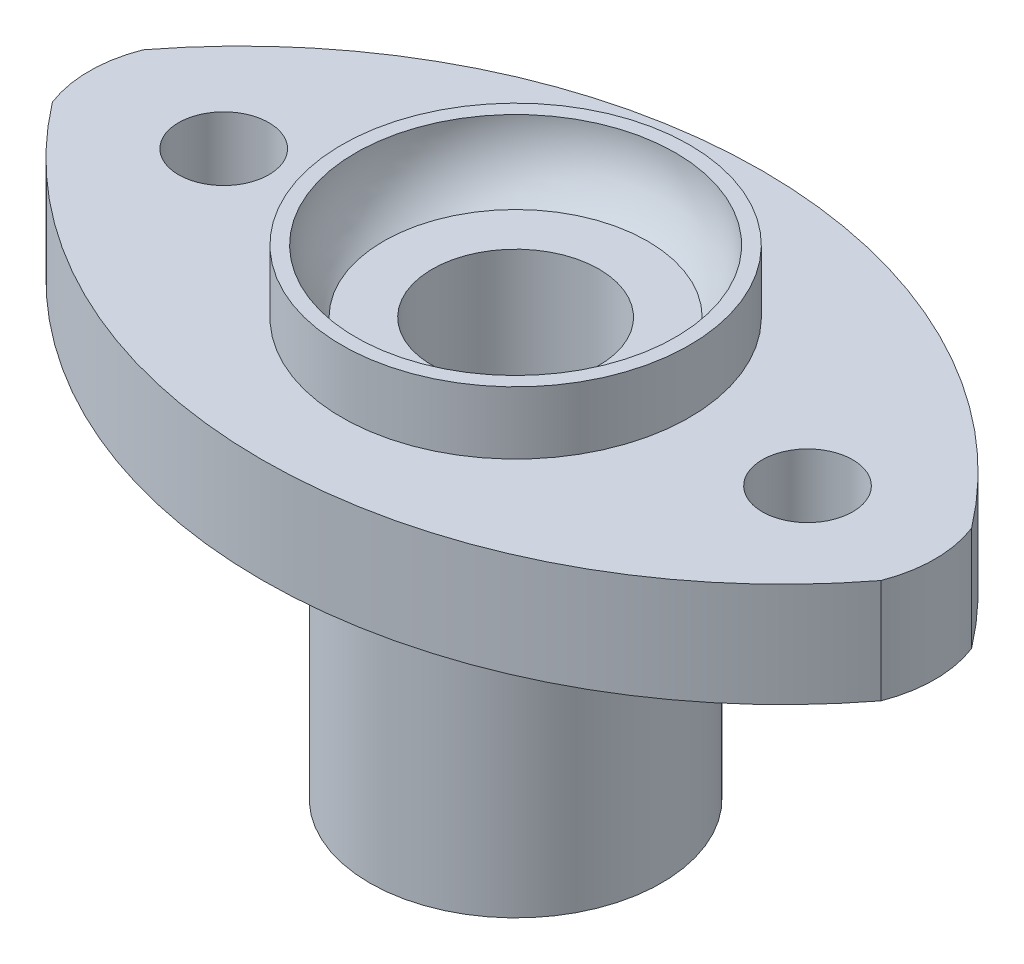
SolidWorks part; units mm, degrees
material "Brass"
ref_plane "Front Plane" through (0, 0, 0) normal (0, 0, 1) x (1, 0, 0)
ref_plane "Top Plane" through (0, 0, 0) normal (0, 1, 0) x (1, 0, 0)
ref_plane "Right Plane" through (0, 0, 0) normal (1, 0, 0) x (0, 0, -1)
sketch "Sketch1" plane through (0, 0, 0) normal (0, 0, 1) x (1, 0, 0)
  line L0 (0, 0) -> (0, 51.0187) construction
  line L1 (12, 0) -> (21, 0)
  line L2 (21, 0) -> (21, 60)
  line L3 (21, 60) -> (25, 60)
  line L4 (25, 60) -> (25, 69)
  line L5 (25, 69) -> (23, 69)
  line L6 (12, 57) -> (12, 0)
  arc A0 (23, 69) -> (12, 57) centre (11.0001, 68.9583) cw
  dimension "D5" = 12
  dimension "D1" = 12
  dimension "D2" = 21
  dimension "D3" = 9
  dimension "D4" = 25
  dimension "D6" = 23
  dimension "D7" = 12
  dimension "D8" = 60
revolve "Revolve1" add sketch "Sketch1" angle 360 about L0
sketch "Sketch2" plane through (0, 60, 0) normal (0, -1, 0) x (1, 0, 0)
  line L0 (0, 0) -> (0, 48.6728) construction
  line L1 (0, 0) -> (-102.5946, 0) construction
  arc A0 (-60.1252, 6.5215) -> (59.0854, 6.5215) centre (-0.5199, -39) cw
  arc A1 (-60.1252, -6.5215) -> (59.0854, -6.5215) centre (-0.5199, 39) ccw
  arc A2 (-60.1252, -6.5215) -> (-60.1252, 6.5215) centre (-43.3482, 0) cw
  arc A3 (59.0854, -6.5215) -> (59.0854, 6.5215) centre (42.3083, 0) ccw
  circle A4 centre (0, 0) radius 12 construction
  circle A5 centre (0, 0) radius 12
  point P11 (-0.5199, 36)
  point P12 (-0.5199, -36)
  dimension "D1" = 75
  dimension "D3" = 18
  dimension "D4" = 18
  dimension "D2" = 72
extrude "Boss-Extrude3" add sketch "Sketch2" along normal blind 15
sketch "Sketch3" plane through (0, 60, 0) normal (0, 1, 0) x (1, 0, 0)
  line L0 (0, 0) -> (0, 32.3057) construction
  point P0 (-42, 0)
  point P4 (0, 0)
  point P5 (42, 0)
  dimension "D1" = 42
hole_wizard "Ø13.0 (13) Diameter Hole1" positions "Sketch4" profile "Sketch5" hole size "Ø13.0" standard "ISO" end condition up to next
sketch "Sketch4" plane through (0, 60, 0) normal (0, 1, 0) x (1, 0, 0)
  point P0 (-42, 0)
  point P3 (42, 0)
sketch "Sketch5" plane through (-42, 60, 0) normal (1, 0, 0) x (0, 0, 1)
  line L0 (0, 0) -> (0, 15)
  line L1 (0, 15) -> (6.5, 15)
  line L2 (6.5, 15) -> (6.5, 0)
  line L5 (6.5, 0) -> (0, 0)
  line L11 (0, -6.35) -> (0, 107.95) construction
  dimension "Thru Hole Dia." = 13
  dimension "Thru Hole Depth" = 15
sketch "Sketch6" plane through (0, 0, 0) normal (0, 0, 1) x (1, 0, 0)
  line L0 (0, 0) -> (0, 14.8858) construction
  line L1 (21, 0) -> (12, 0)
  line L2 (12, 0) -> (12, 2.4115)
  line L3 (12, 0) -> (12, 60) construction
  line L4 (12, 2.4115) -> (21, 0)
  dimension "D1" = 15
revolve "Cut-Revolve5" cut sketch "Sketch6" angle 360 about L0
